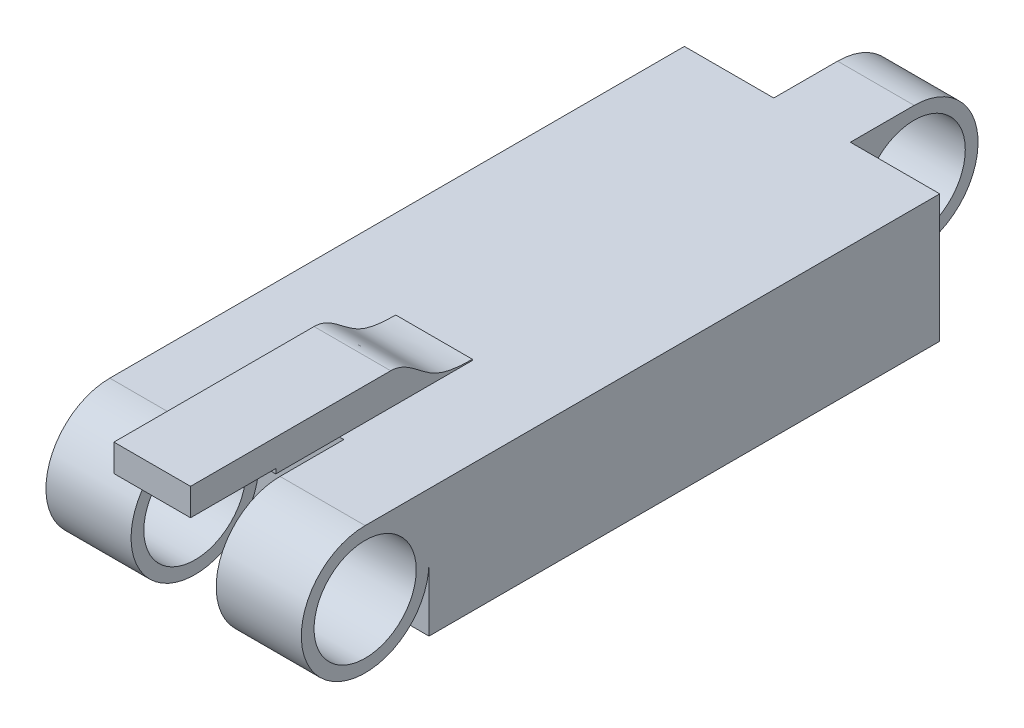
SolidWorks part; units mm, degrees
ref_plane "Front Plane" through (0, 0, 0) normal (0, 0, 1) x (1, 0, 0)
ref_plane "Top Plane" through (0, 0, 0) normal (0, 1, 0) x (1, 0, 0)
ref_plane "Right Plane" through (0, 0, 0) normal (1, 0, 0) x (0, 0, -1)
sketch "Sketch2" plane through (0, 0, 0) normal (1, 0, 0) x (0, 0, -1)
  line L1 (0, 0) -> (20, 0)
  line L2 (0, 0) -> (0, 5)
  line L3 (0, 5) -> (20, 5)
  line L4 (20, 0) -> (20, 5)
  dimension "D1" = 5
  dimension "D2" = 20
extrude "Boss-Extrude1" add sketch "Sketch2" along normal blind 10
sketch "Sketch4" plane through (10, 0, 0) normal (1, 0, 0) x (0, 0, -1)
  line L0 (0, 2.5) -> (-2.5, 2.5) construction
  line L1 (0, 5) -> (0, 0) construction
  line L2 (-2.5, 5) -> (0, 5)
  line L3 (0, 5) -> (0, 2.5)
  arc A0 (-2.5, 5) -> (0, 2.5) centre (-2.5, 2.5) ccw
  circle A1 centre (-2.5, 2.5) radius 2
extrude "Boss-Extrude2" add sketch "Sketch4" against normal blind 3.3333
sketch "Sketch5" plane through (0, 0, 0) normal (-1, 0, 0) x (0, 0, 1)
  line L0 (0, 2.5) -> (2.5, 2.5) construction
  line L1 (0, 5) -> (0, 0) construction
  line L2 (2.5, 5) -> (0, 5)
  line L3 (0, 5) -> (0, 2.5)
  circle A0 centre (2.5, 2.5) radius 2
  arc A1 (0, 2.5) -> (2.5, 5) centre (2.5, 2.5) ccw
extrude "Boss-Extrude3" add sketch "Sketch5" against normal blind 3.3333
sketch "Sketch6" plane through (0, 5, 0) normal (0, 1, 0) x (1, 0, 0)
  line L0 (0, 20) -> (5, 20) construction
  line L1 (10, 20) -> (0, 20) construction
  line L2 (5, 20) -> (5, 16.2794) construction
ref_plane "Plane1" through (5, 0, 0) normal (1, 0, 0) x (0, 0, -1)
sketch "Sketch7" plane through (5, 0, 0) normal (1, 0, 0) x (0, 0, -1)
  line L0 (20, 2.5) -> (22.5, 2.5) construction
  line L1 (20, 0) -> (20, 5) construction
  line L2 (20, 5) -> (22.5, 5)
  line L3 (20, 5) -> (16.2794, 5) construction
  line L4 (20, 5) -> (20, 2.5)
  arc A0 (20, 2.5) -> (22.5, 5) centre (22.5, 2.5) ccw
  circle A1 centre (22.5, 2.5) radius 2
extrude "Boss-Extrude4" add sketch "Sketch7" along normal blind 1.5 and the other way blind 1.5
sketch "Sketch8" plane through (5, 0, 0) normal (1, 0, 0) x (0, 0, -1)
  line L9 (0, 5) -> (2, 5)
  line L10 (20, 5) -> (-2.5, 5) construction
  line L11 (2, 5) -> (5.2, 5)
  line L12 (0, 5) -> (-8, 5)
  line L13 (-8, 5) -> (-8, 6.25)
  line L14 (-8, 6.25) -> (2, 6.25)
  line L15 (5.2, 5) -> (5.2, 5.04)
  spline S0 degree 3 poles (2, 6.25) (2.6337, 6.25) (3.4851, 5.1333) (4.6851, 5.04) (5.2, 5.04) knots 0 0 0 0 0.555541 1 1 1 1
  point P21 (0, 0)
  point P22 (3.4806, 5.5055)
  point P23 (3.6873, 5.2781)
extrude "Boss-Extrude5" add sketch "Sketch8" along normal blind 1.5 and the other way blind 1.5
sketch "Sketch9" plane through (3.5, 0, 0) normal (-1, 0, 0) x (0, 0, 1)
  line L0 (8, 6.25) -> (5.838, 6.25)
  line L1 (-2, 6.25) -> (8, 6.25) construction
  line L2 (5.838, 6.25) -> (5.838, 5.1831)
  line L4 (2.5, 5) -> (2.5, 5.1831)
  line L5 (2.5, 5.1831) -> (5.838, 5.1831)
  line L6 (2.5, 5) -> (8, 5)
  line L7 (8, 5) -> (8, 6.25)
extrude "Cut-Extrude1" cut sketch "Sketch9" against normal through all
